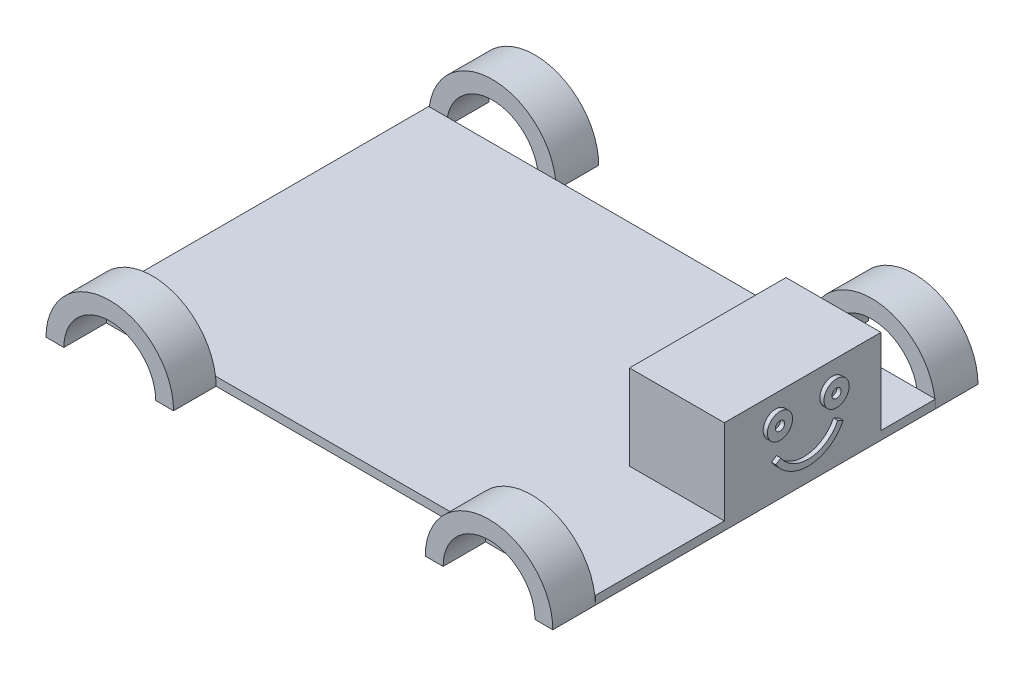
SolidWorks part; units mm, degrees
ref_plane "Front Plane" through (0, 0, 0) normal (0, 0, 1) x (1, 0, 0)
ref_plane "Top Plane" through (0, 0, 0) normal (0, 1, 0) x (1, 0, 0)
ref_plane "Right Plane" through (0, 0, 0) normal (1, 0, 0) x (0, 0, -1)
sketch "Sketch1" plane through (0, 0, 0) normal (0, 0, 1) x (1, 0, 0)
  line L0 (-98.317, 0) -> (85.9751, 0)
  circle A0 centre (0, 0) radius 54
  circle A1 centre (0, 0) radius 75
  dimension "D1" = 108
  dimension "D2" = 150
extrude "Boss-Extrude1" add sketch "Sketch1" along normal blind 50 contours L0 A1 A0
sketch "Sketch2" plane through (0, 0, 0) normal (0, 0, -1) x (-1, 0, 0)
  line L1 (-75, 0) -> (75, 0)
  line L2 (-75, 0) -> (-75, 10)
  line L3 (-75, 10) -> (75, 10)
  line L4 (75, 0) -> (75, 10)
  dimension "D1" = 10
extrude "Boss-Extrude2" add sketch "Sketch2" along normal blind 400
ref_plane "Plane1" through (0, 0, -200) normal (0, 0, -1) x (-1, 0, 0)
mirror "Mirror1" about plane through (0, 0, -200) normal (0, 0, -1) of "Boss-Extrude1"
sketch "Sketch3" plane through (75, 0, 0) normal (1, 0, 0) x (0, 0, -1)
  line L1 (0, 0) -> (400, 0)
  line L2 (0, 0) -> (0, 10)
  line L3 (0, 10) -> (400, 10)
  line L4 (400, 0) -> (400, 10)
extrude "Boss-Extrude3" add sketch "Sketch3" along normal blind 446
ref_plane "Plane2" through (223, 0, 0) normal (-1, 0, 0) x (0, 0, 1)
mirror "Mirror2" about plane through (223, 0, 0) normal (-1, 0, 0) of "Boss-Extrude1", "Mirror1"
sketch "Sketch4" plane through (0, 10, 0) normal (0, 1, 0) x (1, 0, 0)
  line L0 (521, 400) -> (521, 0) construction
  line L1 (521, 335.8333) -> (409.384, 335.8333)
  line L2 (521, 335.8333) -> (521, 151.7503)
  line L3 (521, 151.7503) -> (409.384, 151.7503)
  line L4 (409.384, 335.8333) -> (409.384, 151.7503)
extrude "Boss-Extrude4" add sketch "Sketch4" along normal blind 100
sketch "Sketch5" plane through (521, 0, 0) normal (1, 0, 0) x (0, 0, -1)
  line L0 (280.0033, 50.7037) -> (286.3911, 47.7083)
  line L1 (213.1121, 45.819) -> (207.2272, 41.9274)
  circle A0 centre (212.1548, 79.0419) radius 14.7928
  circle A1 centre (212.1548, 79.0419) radius 5.3977
  circle A2 centre (278.713, 79.0419) radius 14.7928
  circle A3 centre (278.713, 79.0419) radius 5.3977
  arc A4 (207.2272, 41.9274) -> (286.3911, 47.7083) centre (245.1871, 67.03) ccw
  arc A6 (213.1121, 45.819) -> (280.0033, 50.7037) centre (245.1871, 67.03) ccw
extrude "Boss-Extrude5" add sketch "Sketch5" along normal blind 5
